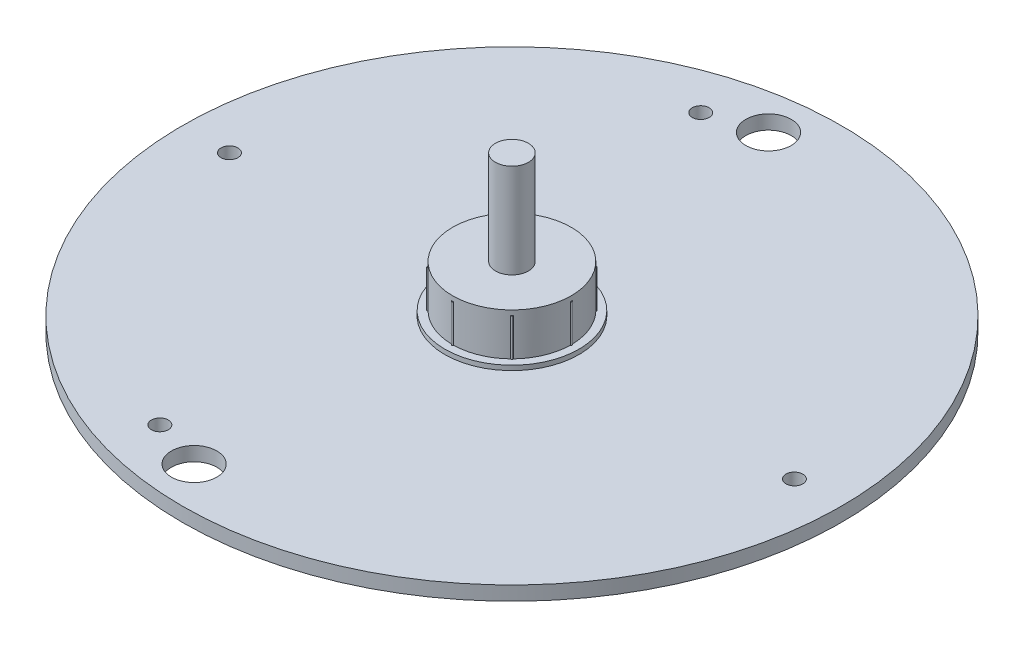
SolidWorks part; units mm, degrees
ref_plane "Front Plane" through (0, 0, 0) normal (0, 0, 1) x (1, 0, 0)
ref_plane "Top Plane" through (0, 0, 0) normal (0, 1, 0) x (1, 0, 0)
ref_plane "Right Plane" through (0, 0, 0) normal (1, 0, 0) x (0, 0, -1)
sketch "Sketch1" plane through (0, 0, 0) normal (0, 1, 0) x (1, 0, 0)
  circle A0 centre (0, 0) radius 70
  dimension "D1" = 140
extrude "base-plate" add sketch "Sketch1" along normal blind 3
sketch "Sketch2" plane through (0, 3, 0) normal (0, 1, 0) x (1, 0, 0)
  circle A0 centre (0, 0) radius 14.25
  dimension "D1" = 28.5
extrude "bearing-stepup" add sketch "Sketch2" along normal blind 1
sketch "Sketch3" plane through (0, 4, 0) normal (0, 1, 0) x (1, 0, 0)
  circle A0 centre (0, 0) radius 12.6
  dimension "D1" = 25.2
extrude "bearing-sitting" add sketch "Sketch3" along normal blind 9
sketch "Sketch4" plane through (0, 4, 0) normal (0, 1, 0) x (1, 0, 0)
  circle A0 centre (0, 12.6) radius 0.2
  circle A1 centre (0, 0) radius 12.6 construction
  circle A2 centre (0, 0) radius 12.6 construction
  circle A3 centre (8.9095, 8.9095) radius 0.2
  circle A4 centre (12.6, 0) radius 0.2
  circle A5 centre (8.9095, -8.9095) radius 0.2
  circle A6 centre (0, -12.6) radius 0.2
  circle A7 centre (-8.9095, -8.9095) radius 0.2
  circle A8 centre (-12.6, 0) radius 0.2
  circle A9 centre (-8.9095, 8.9095) radius 0.2
  point P23 (0, 0)
  dimension "D1" = 0.4
  dimension "D2" = 8
extrude "bearing-sitting-grid" add sketch "Sketch4" along normal blind 8
sketch "Sketch5" plane through (0, 0, 0) normal (0, -1, 0) x (1, 0, 0)
  line L0 (0, 0) -> (0, 42.4646)
  line L1 (0, 0) -> (-17.3419, 57.4392)
  line L2 (7.15, 0) -> (-7.15, 0) construction
  line L3 (0, -7.15) -> (0, 7.15) construction
  circle A0 centre (-17.3419, 57.4392) radius 1.8
  circle A1 centre (-60, 0) radius 1.8
  circle A2 centre (-17.3419, -57.4392) radius 1.8
  circle A3 centre (60, 0) radius 1.8
  dimension "D3" = 3.6
  dimension "D4" = 3.6
  dimension "D1" = 60
  dimension "D2" = 16.8
  dimension "D5" = 60
extrude "m3-screw-clearance-holes" cut sketch "Sketch5" against normal through all
sketch "Sketch6" plane through (0, 0, 0) normal (0, -1, 0) x (1, 0, 0)
  line L0 (7.15, 0) -> (-7.15, 0) construction
  circle A0 centre (-6.5, 61) radius 4.825
  circle A1 centre (-6.5, -61) radius 4.825
  dimension "D3" = 9.65
  dimension "D1" = 61
  dimension "D2" = 6.5
extrude "holes-reserved-for-rods" cut sketch "Sketch6" against normal through all
sketch "Sketch7" plane through (0, 13, 0) normal (0, 1, 0) x (1, 0, 0)
  circle A0 centre (0, 0) radius 3.5
  dimension "D1" = 7
extrude "Boss-Extrude5" add sketch "Sketch7" along normal blind 20
